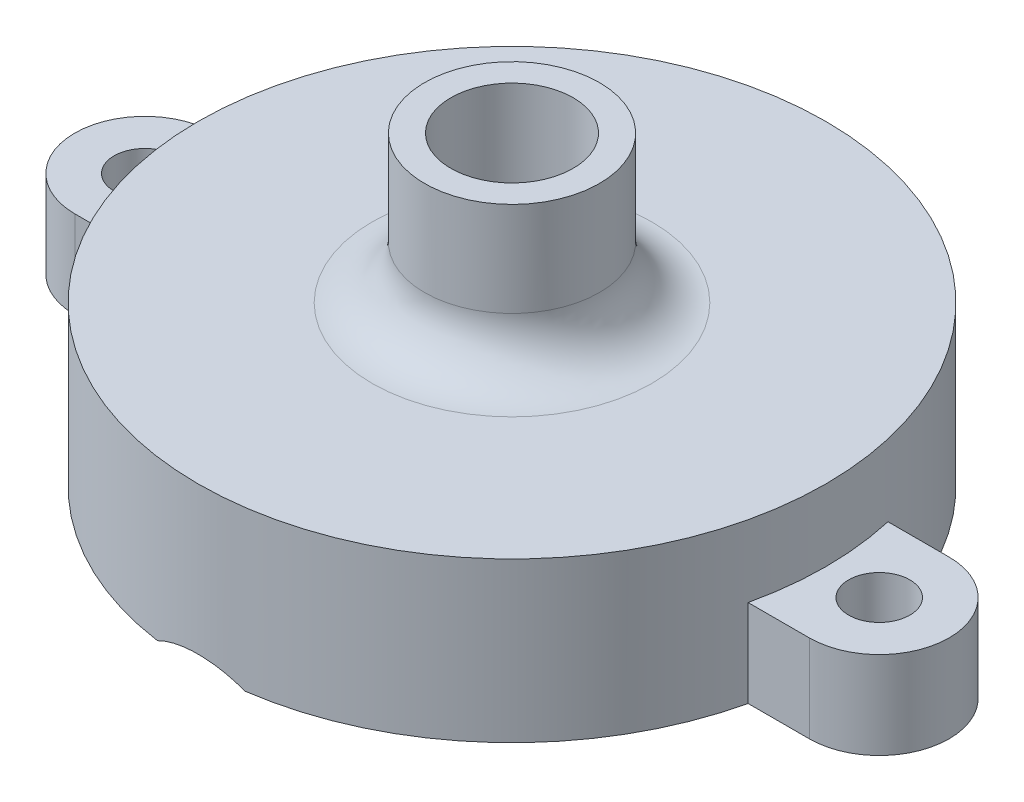
SolidWorks part; units mm, degrees
ref_plane "Front Plane" through (0, 0, 0) normal (0, 0, 1) x (1, 0, 0)
ref_plane "Top Plane" through (0, 0, 0) normal (0, 1, 0) x (1, 0, 0)
ref_plane "Right Plane" through (0, 0, 0) normal (1, 0, 0) x (0, 0, -1)
sketch "Sketch2" plane through (0, 0, 0) normal (0, 0, 1) x (1, 0, 0)
  line L1 (3.5, 6) -> (15.45, 6)
  line L2 (15.45, 6) -> (15.45, 0)
  line L3 (15.45, 0) -> (16.65, 0)
  line L4 (17.95, 0) -> (17.95, 7.6)
  line L5 (17.95, 7.6) -> (5, 7.6)
  line L6 (5, 7.6) -> (5, 16)
  line L7 (5, 16) -> (3.5, 16)
  line L8 (3.5, 16) -> (3.5, 6)
  line L9 (0, 0) -> (0, 50000) construction
  line L10 (16.65, 0) -> (16.65, -1.5)
  line L11 (16.65, -1.5) -> (17.95, -1.5)
  line L12 (17.95, -1.5) -> (17.95, 0)
  dimension "D1" = 6
  dimension "D2" = 2.5
  dimension "D3" = 1.5
  dimension "D4" = 1.6
  dimension "D5" = 30.9
  dimension "D6" = 7
  dimension "D7" = 10
  dimension "D8" = 33.3
  dimension "D9" = 1.5
revolve "Revolve1" add sketch "Sketch2" angle 360 about L9
fillet "Fillet1" radius 3 1 edges at (0, 7.6, -5)
ref_plane "Plane1" through (0, 0, 16.65) normal (0, 0, -1) x (-1, 0, 0)
sketch "Sketch3" plane through (0, 0, 16.65) normal (0, 0, -1) x (-1, 0, 0)
  line L0 (-16.65, 0) -> (16.65, 0) construction
  line L1 (-3.5, 0) -> (3.5, 0)
  line L2 (-3.5, 0) -> (-3.5, -1.5)
  line L3 (-3.5, -1.5) -> (3.5, -1.5)
  line L4 (3.5, 0) -> (3.5, -1.5)
  line L5 (-3.5, 0) -> (3.5, -1.5) construction
  line L6 (-3.5, -1.5) -> (3.5, 0) construction
  line L7 (-16.65, -1.5) -> (16.65, -1.5) construction
  point P0 (0, -0.75)
  dimension "D1" = 7
extrude "Boss-Extrude4" add sketch "Sketch3" along normal up to surface (1.6017 mm away)
sketch "Sketch4" plane through (0, -1.5, 0) normal (0, -1, 0) x (1, 0, 0)
  line L0 (-21, -4) -> (-17.4986, -4)
  line L1 (-21, 4) -> (-17.4986, 4)
  circle A0 centre (-21, 0) radius 1.75
  arc A1 (-21, 4) -> (-21, -4) centre (-21, 0) ccw
  circle A3 centre (0, 0) radius 17.95 construction
  arc A4 (-17.4986, -4) -> (-17.4986, 4) centre (0, 0) cw
  dimension "D1" = 3.5
  dimension "D2" = 4
  dimension "D3" = 21
extrude "Boss-Extrude5" add sketch "Sketch4" against normal blind 5
mirror "Mirror1" about plane through (0, 0, 0) normal (1, 0, 0) of "Boss-Extrude5"
sketch "Sketch5" plane through (0, 0, 16.65) normal (0, 0, -1) x (-1, 0, 0)
  line L0 (-3.5, -1.5) -> (3.5, -1.5) construction
  line L1 (2.5, -1.5) -> (-2.5, -1.5)
  arc A0 (2.5, -1.5) -> (-2.5, -1.5) centre (0, -5.8301) ccw
  dimension "D2" = 5
  dimension "D1" = 1
extrude "Cut-Extrude1" cut sketch "Sketch5" against normal blind 3.19 and the other way blind 3.92
